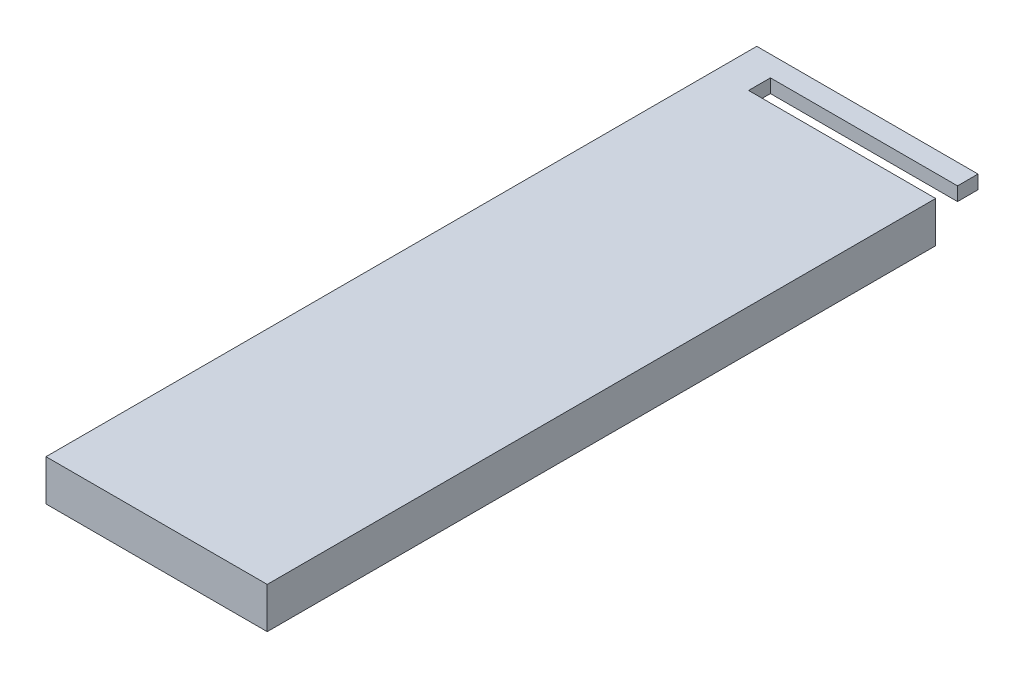
SolidWorks part; units mm, degrees
ref_plane "Front Plane" through (0, 0, 0) normal (0, 0, 1) x (1, 0, 0)
ref_plane "Top Plane" through (0, 0, 0) normal (0, 1, 0) x (1, 0, 0)
ref_plane "Right Plane" through (0, 0, 0) normal (1, 0, 0) x (0, 0, -1)
sketch "Sketch1" plane through (0, 0, 0) normal (0, 1, 0) x (1, 0, 0)
  line L0 (0, 0) -> (30.4, 0)
  line L1 (30.4, 0) -> (30.4, 95.9)
  line L2 (30.4, 95.9) -> (18.2, 95.9)
  line L3 (0, 0) -> (0, 15.7)
  line L6 (18.2, 95.9) -> (18.2, 15.7)
  line L7 (18.2, 15.7) -> (0, 15.7)
  dimension "D1" = 30.4
  dimension "D2" = 95.9
  dimension "D3" = 12.2
  dimension "D4" = 15.7
extrude "Boss-Extrude1" add sketch "Sketch1" along normal blind 2
sketch "Sketch4" plane through (0, 2, 0) normal (0, 1, 0) x (1, 0, 0)
  line L0 (30.4, 95.9) -> (32.4, 95.9)
  line L1 (32.4, 95.9) -> (32.4, 0)
  line L2 (32.4, 0) -> (32.4, -2)
  line L3 (32.4, -2) -> (0, -2)
  line L4 (0, -2) -> (0, 0)
  line L5 (0, 0) -> (30.4, 0)
  line L6 (30.4, 0) -> (30.4, 95.9)
  line L7 (0, -2) -> (-2, -2)
  line L8 (-2, -2) -> (-2, 15.7274)
  line L9 (-2, 15.7274) -> (0, 15.7)
  line M10 (0, 0) -> (30.4, 0)
  line M11 (30.4, 0) -> (30.4, 95.9)
  dimension "D1" = 2
  dimension "D2" = 2
  dimension "D3" = 2
extrude "Boss-Extrude3" add sketch "Sketch4" against normal blind 6 contours L4 L3 L2 L1 L0 M11 M10
sketch "Sketch7" plane through (18.2, 0, 0) normal (-1, 0, 0) x (0, 0, 1)
  line L0 (-95.9, 0) -> (-95.9, 2)
  line L1 (-95.9, 2) -> (-15.7, 2)
  line L2 (-15.7, 2) -> (-15.7, 0)
  line L3 (-15.7, 0) -> (-95.9, 0)
extrude "Boss-Extrude4" add sketch "Sketch7" along normal blind 18.2
sketch "Sketch8" plane through (0, 0, 0) normal (0, -1, 0) x (-1, 0, 0)
  line L0 (0, 95.9) -> (-5, 95.9)
  line L1 (-30.4, 95.9) -> (0, 95.9) construction
  line L2 (-5, 95.9) -> (-5, 99.1)
  line L3 (-32.4, 95.9) -> (-32.4, 99.1)
  line L4 (-32.4, 99.1) -> (-5, 99.1)
  line L5 (-32.4, 99.1) -> (-32.4, 102.1)
  line L6 (-32.4, 102.1) -> (0, 102.1)
  line L7 (0, 102.1) -> (0, 95.9)
  line L8 (-32.4, 102.1) -> (-32.4, 99.1)
  line M4 (0, 95.9) -> (-30.4, 95.9)
  dimension "D1" = 5
  dimension "D2" = 3.2
extrude "Boss-Extrude5" add sketch "Sketch8" against normal blind 2 contours L7 L6 L5 L4 L2 M4
